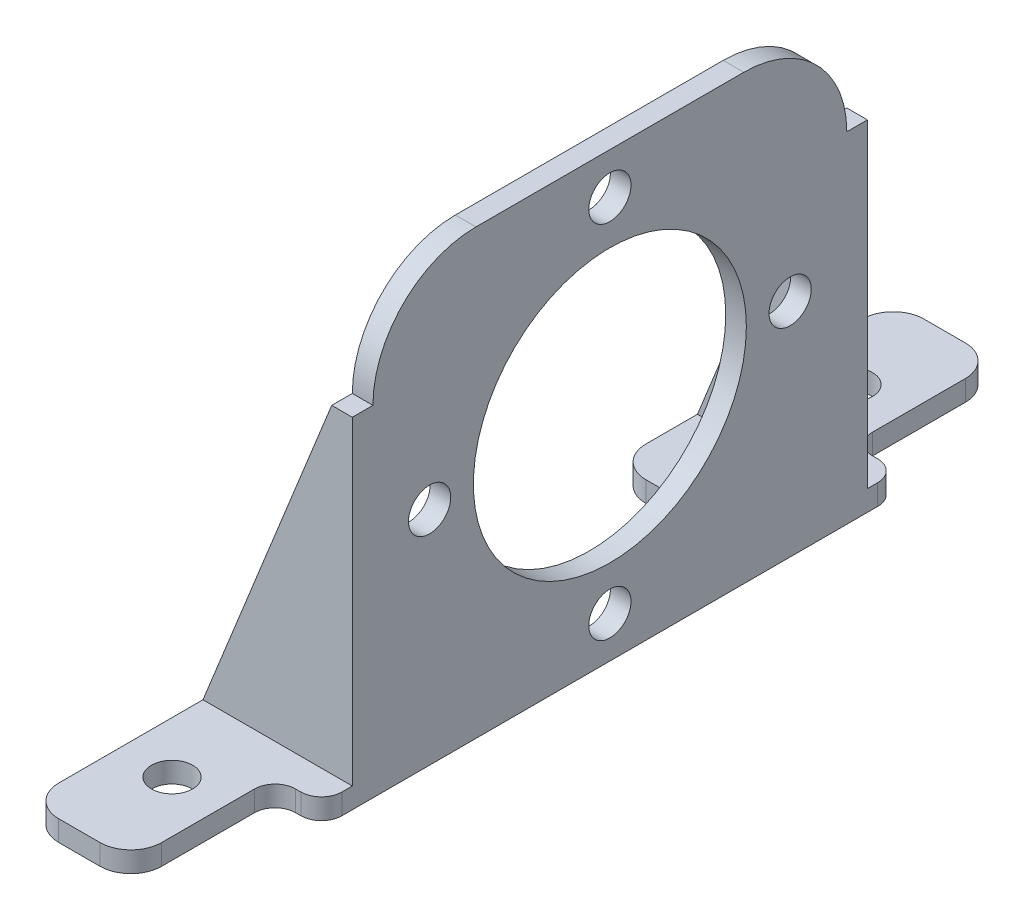
SolidWorks part; units mm, degrees
material "AISI 304"
ref_plane "Front Plane" through (0, 0, 0) normal (0, 0, 1) x (1, 0, 0)
ref_plane "Top Plane" through (0, 0, 0) normal (0, 1, 0) x (1, 0, 0)
ref_plane "Right Plane" through (0, 0, 0) normal (1, 0, 0) x (0, 0, -1)
sketch "Sketch1" plane through (0, 0, 0) normal (1, 0, 0) x (0, 0, -1)
  line L0 (0, 30.6219) -> (0, -32.2275) construction
  line L1 (-35.7829, 0) -> (47.3282, 0) construction
  line L3 (-13, 21.5) -> (13, 21.5)
  line L4 (-23, 11.5) -> (-23, -21.5)
  line L5 (-23, -21.5) -> (23, -21.5)
  line L6 (23, 11.5) -> (23, -21.5)
  line L7 (-23, 21.5) -> (23, -21.5) construction
  line L8 (-23, -21.5) -> (23, 21.5) construction
  circle A1 centre (0, 0) radius 17.5 construction
  circle A2 centre (0, 0) radius 13.25
  circle A3 centre (0, 17.5) radius 2.05
  circle A4 centre (17.5, 0) radius 2.05
  circle A5 centre (0, -17.5) radius 2.05
  circle A6 centre (-17.5, 0) radius 2.05
  arc A7 (13, 21.5) -> (23, 11.5) centre (13, 11.5) cw
  arc A8 (-13, 21.5) -> (-23, 11.5) centre (-13, 11.5) ccw
  dimension "D1" = 10
  dimension "D2" = 35
  dimension "D3" = 26.5
  dimension "D4" = 4.1
  dimension "D5" = 4.1
  dimension "D6" = 4.1
  dimension "D7" = 4.1
  dimension "D8" = 46
  dimension "D9" = 43
extrude "Boss-Extrude1" add sketch "Sketch1" along normal blind 2
sketch "Sketch2" plane through (0, -21.5, 0) normal (0, -1, 0) x (1, 0, 0)
  line L0 (-15.1458, 0) -> (14.7805, 0) construction
  line L2 (-12.5, 23) -> (-12.5, 47)
  line L3 (-12.5, 47) -> (-2.5, 47)
  line L4 (-2.5, 47) -> (-2.5, 28)
  line L5 (0, 23) -> (-31.2254, 23) construction
  line L6 (0, 23) -> (0, -23) construction
  line L7 (-12.5, 35) -> (-7.5, 35) construction
  line L8 (-7.5, 47) -> (-7.5, 23) construction
  line L9 (-7.5, -47) -> (-7.5, -23) construction
  line L10 (-12.5, -35) -> (-7.5, -35) construction
  line L15 (-2.5, 28) -> (2, 28)
  line L16 (2, 28) -> (2, 23)
  line L17 (2, 23) -> (0, 23)
  line L18 (2, -23) -> (0, -23)
  line L19 (2, -28) -> (2, -23)
  line L20 (-2.5, -28) -> (2, -28)
  line L21 (-2.5, -47) -> (-2.5, -28)
  line L22 (-12.5, -47) -> (-2.5, -47)
  line L23 (-12.5, -23) -> (-12.5, -47)
  line L25 (0, -13) -> (0, 13) construction
  line L27 (-12.5, 23) -> (-12.5, 15)
  line L28 (-12.5, 15) -> (0, 15)
  line L29 (0, 23) -> (0, 15)
  line L30 (0, -23) -> (0, -15)
  line L31 (-12.5, -23) -> (-12.5, -15)
  line L32 (-12.5, -15) -> (0, -15)
  circle A1 centre (-7.5, 33) radius 2
  circle A4 centre (-7.5, -33) radius 2
  dimension "D3" = 5
  dimension "D4" = 5
  dimension "D1" = 2.5
  dimension "D5" = 70
  dimension "D6" = 5
  dimension "D8" = 8
  dimension "D9" = 12.5
extrude "Boss-Extrude2" add sketch "Sketch2" against normal blind 2
sketch "Sketch3" plane through (0, 0, -23) normal (0, 0, -1) x (-1, 0, 0)
  line L0 (-2, 11.5) -> (0, 11.5)
  line L1 (0, 11.5) -> (12.5, -19.5)
  line L2 (12.5, -19.5) -> (7.5, -19.5)
  line L3 (12.5, -19.5) -> (2.5, -19.5) construction
  line L10 (-2, -19.55) -> (7.5, -19.5)
  line L11 (-2, 11.5) -> (-2, -19.55)
extrude "Boss-Extrude3" add sketch "Sketch3" along normal blind 2
sketch "Sketch4" plane through (0, 0, 23) normal (0, 0, 1) x (1, 0, 0)
  line L0 (2, 11.5) -> (0, 11.5)
  line L1 (0, 11.5) -> (-12.5, -19.5)
  line L6 (-12.5, -19.5) -> (2, -19.5)
  line L7 (2, -19.5) -> (2, 11.5)
extrude "Boss-Extrude4" add sketch "Sketch4" along normal blind 2
sketch "Sketch6" plane through (0, -19.5, 0) normal (0, 1, 0) x (1, 0, 0)
  line L0 (-12.5, 47) -> (-12.5, 42)
  line L1 (-12.5, 25) -> (-12.5, 47) construction
  line L2 (-12.5, 42) -> (-2.5, 42)
  line L3 (-2.5, 47) -> (-2.5, 28) construction
  line L4 (-2.5, 42) -> (-2.5, 47)
  line L5 (-2.5, 47) -> (-12.5, 47)
  line L6 (-29.5733, 0) -> (8.178, 0) construction
  line L7 (-2.5, -42) -> (-2.5, -47)
  line L8 (-12.5, -42) -> (-2.5, -42)
  line L9 (-12.5, -47) -> (-12.5, -42)
  line L10 (-2.5, -47) -> (-12.5, -47)
  dimension "D1" = 5
extrude "Cut-Extrude2" cut sketch "Sketch6" against normal blind 2
fillet "Fillet1" radius 3 4 edges at (-2.5, -20.5, 42) (-12.5, -20.5, 42) (-12.5, -20.5, -42) (-2.5, -20.5, -42)
fillet "圆角1" radius 2 4 edges at (-2.5, -20.5, 28) (2, -20.5, 28) (2, -20.5, -28) (-2.5, -20.5, -28)
fillet "圆角2" radius 3 2 edges at (-12.5, -20.5, 15) (-12.5, -20.5, -15)
